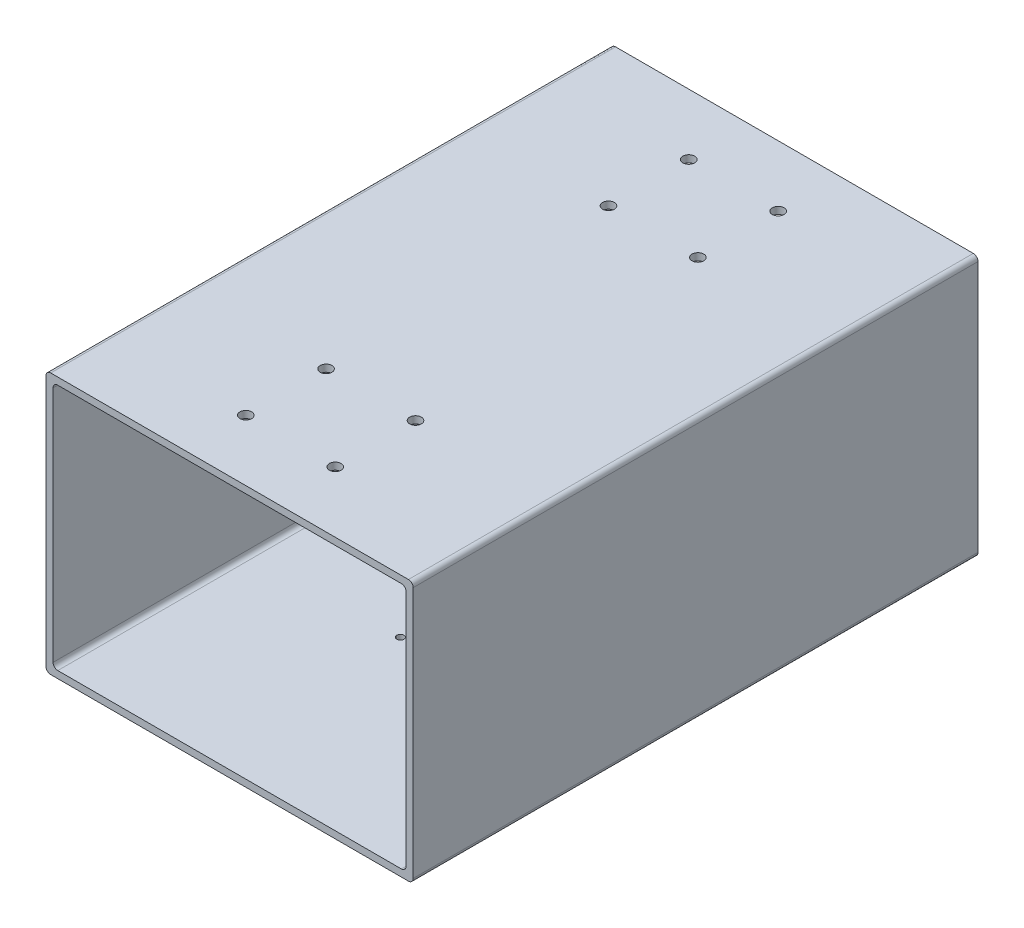
SolidWorks part; units mm, degrees
ref_plane "Front Plane" through (0, 0, 0) normal (0, 0, 1) x (1, 0, 0)
ref_plane "Top Plane" through (0, 0, 0) normal (0, 1, 0) x (1, 0, 0)
ref_plane "Right Plane" through (0, 0, 0) normal (1, 0, 0) x (0, 0, -1)
sketch "Sketch1" plane through (0, 0, 0) normal (0, 0, 1) x (1, 0, 0)
  line L1 (75, -52.5) -> (-75, -52.5)
  line L2 (75, -52.5) -> (75, 52.5)
  line L3 (75, 52.5) -> (-75, 52.5)
  line L4 (-75, -52.5) -> (-75, 52.5)
  line L5 (75, -52.5) -> (-75, 52.5) construction
  line L6 (75, 52.5) -> (-75, -52.5) construction
  point P0 (0, 0)
  dimension "D1" = 150
  dimension "D2" = 105
extrude "Extrude-Thin1" add sketch "Sketch1" along normal mid plane 240 thin thin type one direction wall 3
fillet "Fillet1" radius 2 8 edges at (-75, -52.5, 0) (75, -52.5, 0) (75, 52.5, 0) (-75, 52.5, 0) (78, -55.5, 0) (-78, -55.5, 0) (78, 55.5, 0) (-78, 55.5, 0)
sketch "Sketch4" plane through (0, 55.5, 0) normal (0, 1, 0) x (1, 0, 0)
  line L1 (19, -60) -> (-19, -60) construction
  line L2 (19, -60) -> (19, 60) construction
  line L3 (19, 60) -> (-19, 60) construction
  line L4 (-19, -60) -> (-19, 60) construction
  line L5 (19, -60) -> (-19, 60) construction
  line L6 (19, 60) -> (-19, -60) construction
  line L7 (19, -94.1) -> (-19, -94.1) construction
  line L8 (19, -94.1) -> (19, 94.1) construction
  line L9 (19, 94.1) -> (-19, 94.1) construction
  line L10 (-19, -94.1) -> (-19, 94.1) construction
  line L11 (19, -94.1) -> (-19, 94.1) construction
  line L12 (19, 94.1) -> (-19, -94.1) construction
  point P0 (0, 0)
  point P6 (0, 0)
  dimension "D1" = 34.1
  dimension "D2" = 120
  dimension "D3" = 38
  dimension "D4" = 38
sketch "Sketch5" plane through (0, 55.5, 0) normal (0, 1, 0) x (1, 0, 0)
  circle A0 centre (-19, 60) radius 2.5
  circle A1 centre (19, 60) radius 2.5
  circle A2 centre (19, -60) radius 2.5
  circle A3 centre (-19, -60) radius 2.5
  circle A4 centre (-19, 94.1) radius 2.5
  circle A5 centre (19, 94.1) radius 2.5
  circle A6 centre (19, -94.1) radius 2.5
  circle A7 centre (-19, -94.1) radius 2.5
  dimension "D1" = 5
  dimension "D2" = 5
  dimension "D3" = 5
  dimension "D4" = 5
extrude "Cut-Extrude1" cut sketch "Sketch5" against normal up to next and the other way through all
sketch "Sketch6" plane through (0, -55.5, 0) normal (0, -1, 0) x (-1, 0, 0)
  line L1 (12.475, -34.95) -> (-12.475, -34.95) construction
  line L2 (12.475, -34.95) -> (12.475, 34.95) construction
  line L3 (12.475, 34.95) -> (-12.475, 34.95) construction
  line L4 (-12.475, -34.95) -> (-12.475, 34.95) construction
  line L5 (12.475, -34.95) -> (-12.475, 34.95) construction
  line L6 (12.475, 34.95) -> (-12.475, -34.95) construction
  point P0 (0, 0)
  dimension "D1" = 69.9
  dimension "D2" = 24.95
sketch "Sketch7" plane through (0, -55.5, 0) normal (0, -1, 0) x (-1, 0, 0)
  circle A0 centre (-12.475, -34.95) radius 1.5
  circle A1 centre (12.475, -34.95) radius 1.5
  circle A2 centre (-12.475, 34.95) radius 1.5
  circle A3 centre (12.475, 34.95) radius 1.5
extrude "Cut-Extrude2" cut sketch "Sketch7" against normal up to next and the other way through all
